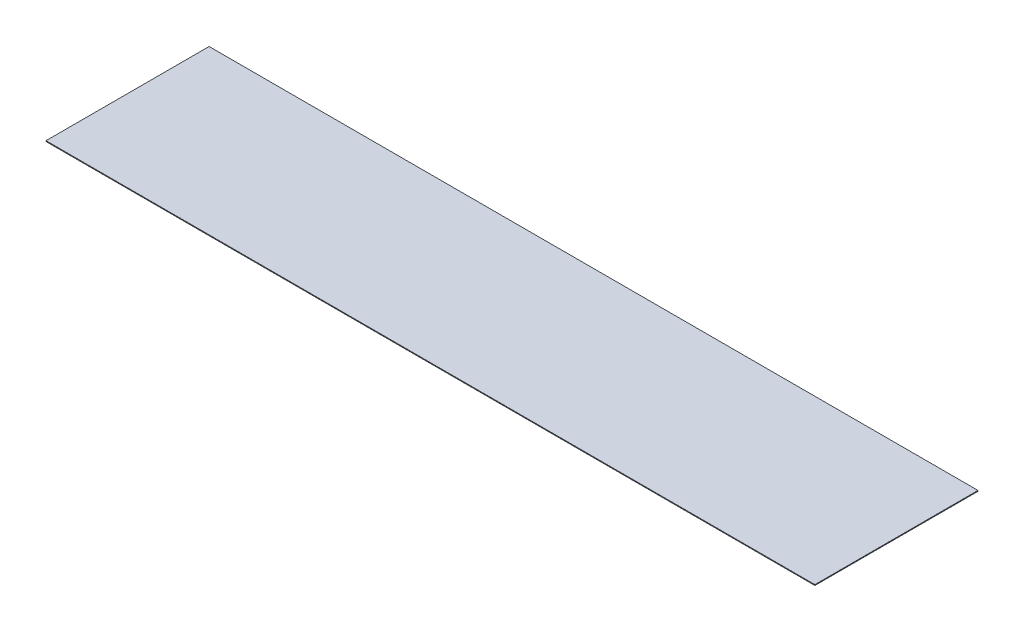
SolidWorks part; units mm, degrees
ref_plane "Alzado" through (0, 0, 0) normal (0, 0, 1) x (1, 0, 0)
ref_plane "Planta" through (0, 0, 0) normal (0, 1, 0) x (1, 0, 0)
ref_plane "Vista lateral" through (0, 0, 0) normal (1, 0, 0) x (0, 0, -1)
sketch "Croquis1" plane through (0, 0, 0) normal (0, 1, 0) x (1, 0, 0)
  line L1 (-49.5, 10.5) -> (49.5, 10.5)
  line L2 (-49.5, 10.5) -> (-49.5, -10.5)
  line L3 (-49.5, -10.5) -> (49.5, -10.5)
  line L4 (49.5, 10.5) -> (49.5, -10.5)
  line L5 (-49.5, 10.5) -> (49.5, -10.5) construction
  line L6 (-49.5, -10.5) -> (49.5, 10.5) construction
  point P0 (0, 0)
  dimension "D1" = 99
  dimension "D2" = 21
extrude "Saliente-Extruir1" add sketch "Croquis1" along normal blind 0.1
